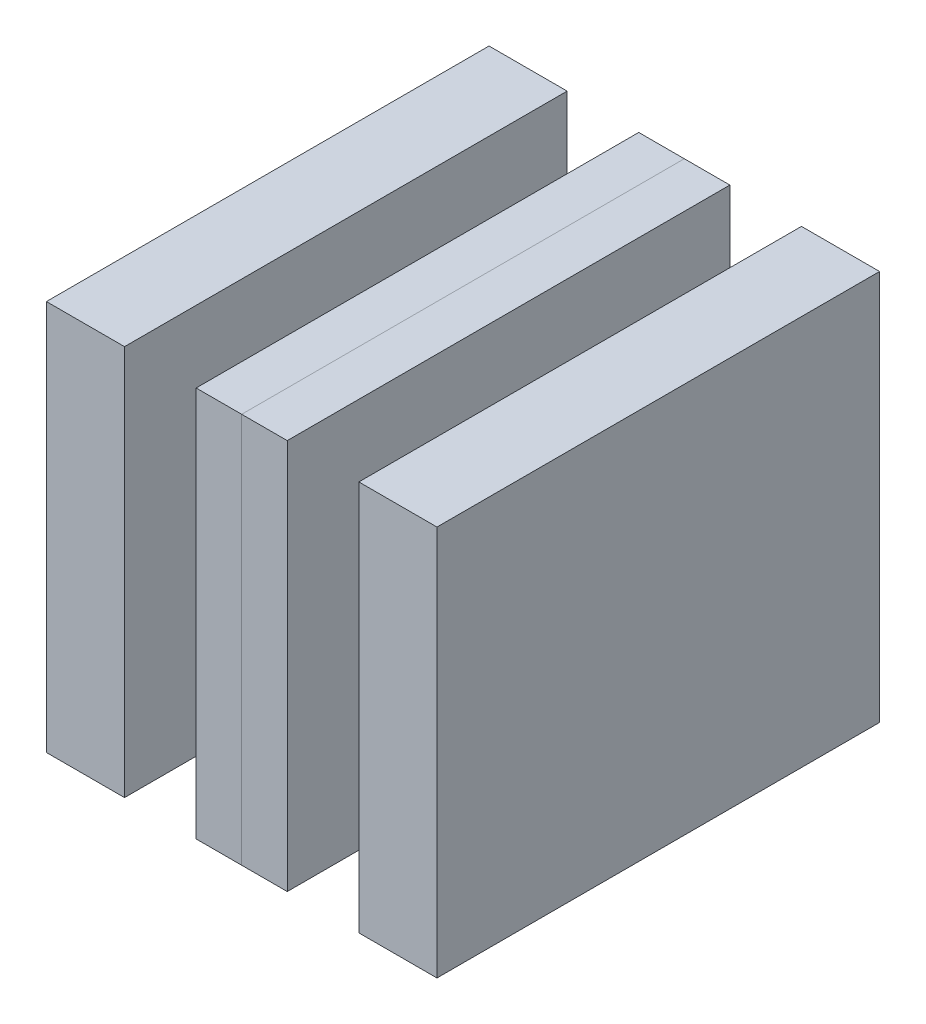
SolidWorks part; units mm, degrees
ref_plane "Front Plane" through (0, 0, 0) normal (0, 0, 1) x (1, 0, 0)
ref_plane "Top Plane" through (0, 0, 0) normal (0, 1, 0) x (1, 0, 0)
ref_plane "Right Plane" through (0, 0, 0) normal (1, 0, 0) x (0, 0, -1)
sketch "Sketch1" plane through (0, 0, 0) normal (0, 0, 1) x (1, 0, 0)
  line L1 (0, 0) -> (3, 0)
  line L2 (0, 0) -> (0, 15)
  line L3 (0, 15) -> (3, 15)
  line L4 (3, 0) -> (3, 15)
  line L5 (5.75, 15) -> (7.5, 15)
  line L6 (5.75, 15) -> (5.75, 0)
  line L7 (5.75, 0) -> (7.5, 0)
  line L8 (7.5, 15) -> (7.5, 0)
  dimension "D1" = 15
  dimension "D2" = 1.75
  dimension "D3" = 4.5
  dimension "D4" = 7.5
extrude "Boss-Extrude1" add sketch "Sketch1" along normal blind 17
mirror "Mirror1" about plane through (7.5, 15, 17) normal (-1, 0, 0) of bodies 102 101
